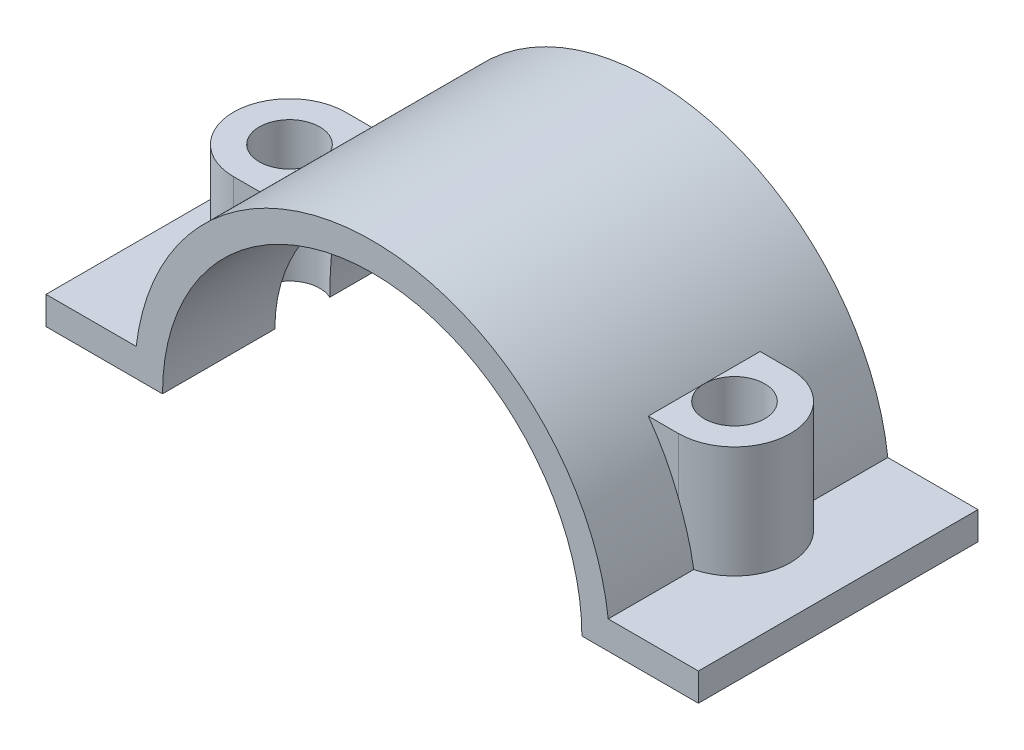
SolidWorks part; units mm, degrees
ref_plane "Front Plane" through (0, 0, 0) normal (0, 0, 1) x (1, 0, 0)
ref_plane "Top Plane" through (0, 0, 0) normal (0, 1, 0) x (1, 0, 0)
ref_plane "Right Plane" through (0, 0, 0) normal (1, 0, 0) x (0, 0, -1)
sketch "Sketch2" plane through (0, 0, 0) normal (0, 0, 1) x (1, 0, 0)
  line L0 (-22.5, 0) -> (-35, 0)
  line L1 (0, 0) -> (0, 51.3185) construction
  line L2 (22.5, 0) -> (35, 0)
  line L3 (25.3229, 3) -> (35, 3)
  line L4 (-25.3229, 3) -> (-35, 3)
  line L5 (-35, 3) -> (-35, 0)
  line L6 (35, 3) -> (35, 0)
  arc A0 (22.5, 0) -> (-22.5, 0) centre (0, 0) ccw
  arc A1 (25.3229, 3) -> (-25.3229, 3) centre (0, 0) ccw
  dimension "D1" = 45
  dimension "D2" = 35
  dimension "D3" = 3
extrude "Boss-Extrude4" add sketch "Sketch2" along normal mid plane 30
ref_plane "Plane3" through (0, 15, 0) normal (0, 1, 0) x (1, 0, 0)
sketch "Sketch5" plane through (0, 15, 0) normal (0, 1, 0) x (1, 0, 0)
  line L0 (0, 0) -> (-35, 0) construction
  line L1 (-35, -15) -> (-35, 15) construction
  line L7 (-23.8728, 6) -> (-13.8728, 6)
  line L9 (-23.8728, -6) -> (-13.8728, -6)
  line L10 (-13.8728, 6) -> (-13.8728, -6)
  arc A0 (-23.8728, 6) -> (-23.8728, -6) centre (-23.8728, 0) ccw
  dimension "D1" = 12
  dimension "D2" = 10
extrude "Boss-Extrude5" add sketch "Sketch5" against normal up to body separate body
sketch "Sketch8" plane through (0, 15, 0) normal (0, 1, 0) x (1, 0, 0)
  circle A1 centre (-23.8728, 0) radius 3.25
  dimension "D1" = 6.5
extrude "Cut-Extrude1" cut sketch "Sketch8" against normal through all
mirror "Mirror1" about plane through (0, 0, 0) normal (1, 0, 0) of "Boss-Extrude5"
mirror "Mirror2" about plane through (0, 0, 0) normal (1, 0, 0) of "Cut-Extrude1"
